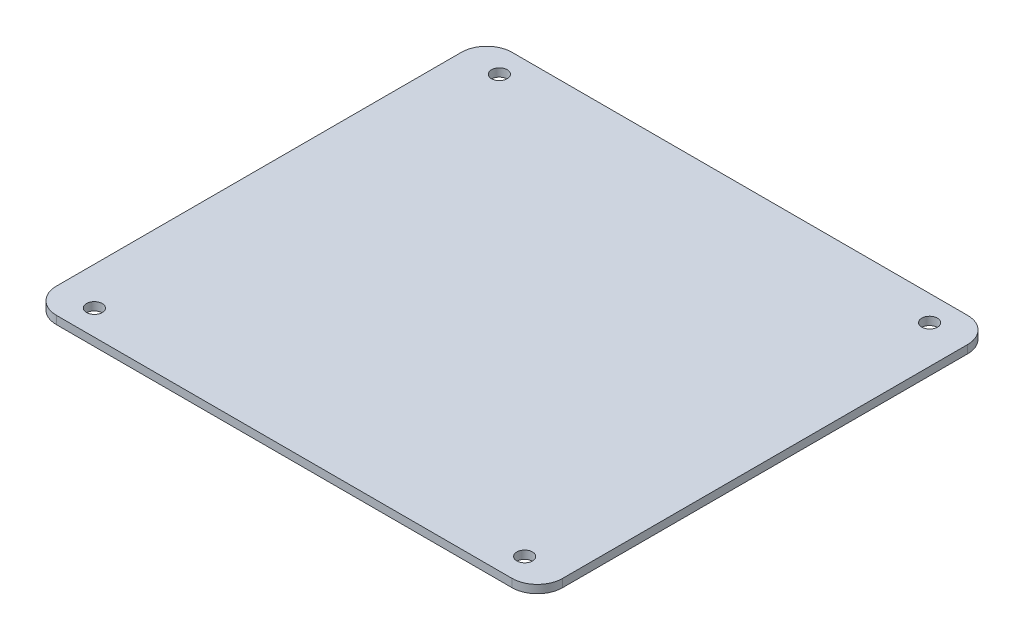
SolidWorks part; units mm, degrees
ref_plane "前视基准面" through (0, 0, 0) normal (0, 0, 1) x (1, 0, 0)
ref_plane "上视基准面" through (0, 0, 0) normal (0, 1, 0) x (1, 0, 0)
ref_plane "右视基准面" through (0, 0, 0) normal (1, 0, 0) x (0, 0, -1)
other "Configuration Table"
sketch "草图1" plane through (0, 0, 0) normal (0, 1, 0) x (1, 0, 0)
  line L1 (-42.5, -40) -> (42.5, -40) construction
  line L2 (-42.5, -40) -> (-42.5, 40) construction
  line L3 (-42.5, 40) -> (42.5, 40) construction
  line L4 (42.5, -40) -> (42.5, 40) construction
  line L5 (-42.5, -40) -> (42.5, 40) construction
  line L6 (-42.5, 40) -> (42.5, -40) construction
  line L7 (50, -45) -> (-50, -45)
  line L8 (50, -45) -> (50, 45)
  line L9 (50, 45) -> (-50, 45)
  line L10 (-50, -45) -> (-50, 45)
  line L11 (50, -45) -> (-50, 45) construction
  line L12 (50, 45) -> (-50, -45) construction
  circle A0 centre (-42.5, 40) radius 1.55
  circle A1 centre (42.5, 40) radius 1.55
  circle A2 centre (-42.5, -40) radius 1.55
  circle A3 centre (42.5, -40) radius 1.55
  point P0 (0, 0)
  point P10 (0, 0)
  dimension "D1" = 3.1
  dimension "D2" = 3.1
  dimension "D3" = 3.1
  dimension "D4" = 3.1
  dimension "D5" = 85
  dimension "D6" = 80
  dimension "D7" = 100
  dimension "D8" = 90
extrude "凸台-拉伸1" add sketch "草图1" along normal blind 1.6
fillet "圆角1" radius 5 4 edges at (50, 0.8, -45) (50, 0.8, 45) (-50, 0.8, 45) (-50, 0.8, -45)
